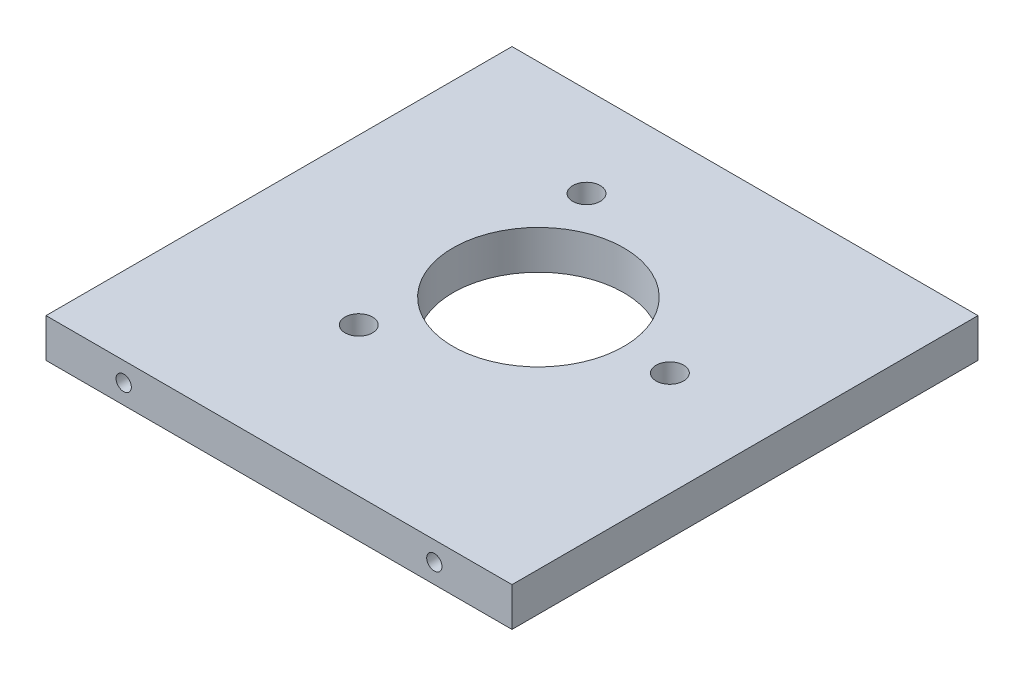
SolidWorks part; units mm, degrees
material "6061 Alloy"
ref_plane "Front Plane" through (0, 0, 0) normal (0, 0, 1) x (1, 0, 0)
ref_plane "Top Plane" through (0, 0, 0) normal (0, 1, 0) x (1, 0, 0)
ref_plane "Right Plane" through (0, 0, 0) normal (1, 0, 0) x (0, 0, -1)
sketch "Sketch1" plane through (0, 0, 0) normal (0, 0, 1) x (1, 0, 0)
  line L0 (0, 3.175) -> (0, -3.175)
  line L1 (-38.1, 0) -> (38.1, 0) construction
  point P6 (0, 0)
  dimension "Width" = 76.2
  dimension "Thk" = 6.35
sketch "Sketch2" plane through (0, 0, 0) normal (1, 0, 0) x (0, 0, -1)
  line L0 (76.2, 0) -> (-76.2, 0)
  point P4 (0, 0)
  dimension "Length" = 152.4
sketch "Sketch3" plane through (0, 0, 0) normal (0, 0, 1) x (1, 0, 0)
  line L1 (38.1, 3.175) -> (-38.1, 3.175)
  line L2 (38.1, 3.175) -> (38.1, -3.175)
  line L3 (38.1, -3.175) -> (-38.1, -3.175)
  line L4 (-38.1, 3.175) -> (-38.1, -3.175)
  line L5 (38.1, 3.175) -> (-38.1, -3.175) construction
  line L6 (38.1, -3.175) -> (-38.1, 3.175) construction
  point P0 (0, 0)
extrude "Boss-Extrude1" add sketch "Sketch3" along normal up to vertex (76.2 mm away) and the other way up to vertex (76.2 mm away) up to point (0, 0, 76.2) other way up to point (0, 0, -76.2)
sketch "Sketch4" plane through (0, 3.175, 0) normal (0, 1, 0) x (1, 0, 0)
  point P1 (0, -1.15)
hole_wizard "M8 Clearance Hole1" [suppressed] positions "Sketch5" profile "Sketch6" hole size "M8" standard "ANSI Metric"
sketch "Sketch5" plane through (0, 3.175, 0) normal (0, 1, 0) x (1, 0, 0)
  point P8 (0, -1.15)
sketch "Sketch6" plane through (0, 3.175, 1.15) normal (1, 0, 0) x (0, 0, 1)
  line L0 (0, 0) -> (0, 6.35)
  line L1 (0, 6.35) -> (4.5, 6.35)
  line L2 (4.5, 6.35) -> (4.5, 0)
  line L5 (4.5, 0) -> (0, 0)
  line L11 (0, -6.35) -> (0, 107.95) construction
  dimension "Thru Hole Dia." = 9
  dimension "Thru Hole Depth" = 6.35
sketch "Sketch7" plane through (0, 3.175, 0) normal (0, 1, 0) x (1, 0, 0)
  point P0 (-8.2489, -5.9125)
  point P1 (0, -10.675)
  point P3 (8.2489, -5.9125)
  point P5 (8.2489, 3.6125)
  point P7 (0, 8.375)
  point P9 (-8.2489, 3.6125)
hole_wizard "CSK for M3 Flat Head Machine Screw1" [suppressed] positions "Sketch8" profile "Sketch10" countersink size "M3" standard "ANSI Metric"
sketch "Sketch8" plane through (0, 3.175, 0) normal (0, 1, 0) x (1, 0, 0)
  point P0 (-8.2489, -5.9125)
  point P3 (0, -10.675)
  point P6 (8.2489, -5.9125)
  point P9 (8.2489, 3.6125)
  point P12 (0, 8.375)
  point P15 (-8.2489, 3.6125)
sketch "Sketch10" plane through (-8.2489, -3.175, 5.9125) normal (1, 0, 0) x (0, 0, -1)
  line L0 (0, 0) -> (0, 6.35)
  line L1 (0, 6.35) -> (1.7, 6.35)
  line L2 (1.7, 6.35) -> (1.7, 1.45)
  line L3 (1.7, 1.45) -> (3.15, 0)
  line L5 (3.15, 0) -> (0, 0)
  line L6 (-1.7, 1.45) -> (-3.15, 0) construction
  line L11 (0, -6.35) -> (0, 107.95) construction
  dimension "Thru Hole Dia." = 3.4
  dimension "Thru Hole Depth" = 6.35
  dimension "Near C'Sink Dia." = 6.3
  dimension "Near C'Sink Angle" = 90
sketch "Sketch11" plane through (0, -3.175, 0) normal (0, -1, 0) x (1, 0, 0)
  circle A0 centre (-0.451, 33.3341) radius 13.97
  point P0 (-0.451, 33.3341)
  dimension "D1" = 27.94
extrude "Cut-Extrude1" cut sketch "Sketch11" against normal through all
sketch "Sketch12" plane through (0, -3.175, 0) normal (0, -1, 0) x (1, 0, 0)
  point P0 (-11.201, 14.7145)
  point P1 (21.049, 33.3341)
  point P3 (-11.201, 51.9536)
hole_wizard "CSK for M4 Flat Head Machine Screw1" positions "Sketch13" profile "Sketch14" countersink size "M4" standard "ANSI Metric" end condition through all
sketch "Sketch13" plane through (0, -3.175, 0) normal (0, -1, 0) x (-1, 0, 0)
  point P0 (11.201, -14.7145)
  point P3 (-21.049, -33.3341)
  point P6 (11.201, -51.9536)
sketch "Sketch14" plane through (-11.201, -3.175, 14.7145) normal (1, 0, 0) x (0, 0, -1)
  line L0 (0, 0) -> (0, 6.35)
  line L1 (0, 6.35) -> (2.25, 6.35)
  line L2 (2.25, 6.35) -> (2.25, 2.45)
  line L3 (2.25, 2.45) -> (4.7, 0)
  line L5 (4.7, 0) -> (0, 0)
  line L6 (-2.25, 2.45) -> (-4.7, 0) construction
  line L11 (0, -6.35) -> (0, 107.95) construction
  dimension "Thru Hole Dia." = 4.5
  dimension "Thru Hole Depth" = 6.35
  dimension "Near C'Sink Dia." = 9.4
  dimension "Near C'Sink Angle" = 90
sketch "Sketch15" plane through (0, -3.175, 0) normal (0, -1, 0) x (1, 0, 0)
  point P0 (-0.451, 33.3341)
hole_wizard "Ø12.0mm Dowel Hole1" [suppressed] positions "Sketch18" profile "Sketch19" hole size "Ø12.0" standard "ANSI Metric"
sketch "Sketch18" plane through (0, -3.175, 0) normal (0, -1, 0) x (-1, 0, 0)
  point P0 (0.451, -31.8101)
sketch "Sketch19" plane through (-0.451, -3.175, 31.8101) normal (1, 0, 0) x (0, 0, -1)
  line L0 (0, 0) -> (0, 6.35)
  line L1 (0, 6.35) -> (6, 6.35)
  line L2 (6, 6.35) -> (6, 0)
  line L5 (6, 0) -> (0, 0)
  line L11 (0, -6.35) -> (0, 107.95) construction
  dimension "Thru Hole Dia." = 12
  dimension "Thru Hole Depth" = 6.35
sketch "Sketch20" plane through (0, -3.175, 0) normal (0, -1, 0) x (1, 0, 0)
  line L0 (-38.1, 76.2) -> (-38.1, -76.2) construction
  line L1 (38.1, -76.2) -> (-38.1, -76.2)
  line L2 (38.1, -76.2) -> (38.1, 0)
  line L3 (38.1, 0) -> (-38.1, 0)
  line L4 (-38.1, -76.2) -> (-38.1, 0)
  line L5 (-38.1, 76.2) -> (38.1, 76.2) construction
  dimension "D1" = 76.2
extrude "Cut-Extrude2" cut sketch "Sketch20" against normal through all
sketch "Sketch21" plane through (0, 3.175, 0) normal (0, 1, 0) x (1, 0, 0)
  circle A0 centre (0.6258, -38.1) radius 13.97
  point P0 (0.6258, -38.1)
  dimension "D1" = 27.94
extrude "Cut-Extrude3" [suppressed] cut sketch "Sketch21" against normal through all
sketch "Sketch22" plane through (0, 3.175, 0) normal (0, 1, 0) x (1, 0, 0)
  point P0 (0.6258, -59.6)
  point P1 (-17.9937, -27.35)
  point P3 (19.2454, -27.35)
hole_wizard "CSK for M4 Flat Head Machine Screw2" [suppressed] positions "Sketch23" profile "Sketch25" countersink size "M4" standard "ANSI Metric"
sketch "Sketch23" plane through (0, 3.175, 0) normal (0, 1, 0) x (1, 0, 0)
  point P0 (0.6258, -59.6)
  point P3 (19.2454, -27.35)
  point P6 (-17.9937, -27.35)
sketch "Sketch25" plane through (0.6258, 3.175, 59.6) normal (1, 0, 0) x (0, 0, 1)
  line L0 (0, 0) -> (0, 6.35)
  line L1 (0, 6.35) -> (2.25, 6.35)
  line L2 (2.25, 6.35) -> (2.25, 2.45)
  line L3 (2.25, 2.45) -> (4.7, 0)
  line L5 (4.7, 0) -> (0, 0)
  line L6 (-2.25, 2.45) -> (-4.7, 0) construction
  line L11 (0, -6.35) -> (0, 107.95) construction
  dimension "Thru Hole Dia." = 4.5
  dimension "Thru Hole Depth" = 6.35
  dimension "Near C'Sink Dia." = 9.4
  dimension "Near C'Sink Angle" = 90
sketch "Sketch26" [suppressed] plane through (0, 3.175, 0) normal (0, 1, 0) x (1, 0, 0)
  line L0 (38.1, -76.2) -> (38.1, 76.2) construction
  line L1 (-38.1, -76.2) -> (38.1, -76.2)
  line L2 (-38.1, -76.2) -> (-38.1, 25.4)
  line L3 (-38.1, 25.4) -> (38.1, 25.4)
  line L4 (38.1, -76.2) -> (38.1, 25.4)
  line L5 (38.1, 76.2) -> (-38.1, 76.2) construction
  dimension "D1" = 50.8
extrude "Cut-Extrude4" [suppressed] cut sketch "Sketch26" against normal through all contours L3 L4 L1 L2
sketch "Sketch27" [suppressed] plane through (-38.1, 0, 0) normal (-1, 0, 0) x (0, 0, 1)
  line L0 (-63.5, 0) -> (-38.1, 0) construction
  line L1 (-25.4, 3.175) -> (-76.2, 3.175) construction
  line L2 (-76.2, 3.175) -> (-76.2, -3.175) construction
  point P0 (-63.5, 0)
  point P1 (-38.1, 0)
  point P4 (-50.8, 0)
  point P7 (-50.8, 3.175)
  point P10 (-76.2, 0)
  dimension "D1" = 25.4
sketch "Sketch31" [suppressed] plane through (0, 3.175, 0) normal (0, 1, 0) x (1, 0, 0)
  line L0 (38.1, 76.2) -> (-38.1, 76.2) construction
  line L1 (38.1, 25.4) -> (5.08, 25.4)
  line L2 (38.1, 25.4) -> (38.1, 76.2)
  line L3 (38.1, 76.2) -> (5.08, 76.2)
  line L4 (5.08, 25.4) -> (5.08, 76.2)
  line L5 (-38.1, 25.4) -> (-38.1, 76.2) construction
  dimension "D1" = 43.18
extrude "Cut-Extrude5" [suppressed] cut sketch "Sketch31" against normal through all
hole_wizard "M3x0.5 Tapped Hole1" [suppressed] positions "Sketch28" profile "Sketch30" tap size "M3x0.5" standard "ANSI Metric"
sketch "Sketch28" [suppressed] plane through (-38.1, 0, 0) normal (-1, 0, 0) x (0, 0, 1)
  point P0 (-63.5, 0)
  point P3 (-38.1, 0)
cosmetic thread "Hole Thread1" [suppressed] parameters "D1"=4.0005, "D2"=3
cosmetic thread "Hole Thread2" [suppressed] parameters "D1"=4.0005, "D2"=3
sketch "Sketch30" plane through (-38.1, 0, -63.5) normal (0, 1, 0) x (0, 0, 1)
  line L0 (0, 0) -> (0, 6.35)
  line L1 (0, 6.35) -> (1.25, 5.5989)
  line L2 (1.25, 5.5989) -> (1.25, 0)
  line L5 (1.25, 0) -> (0, 0)
  line L10 (0, 6.35) -> (-1.25, 5.5989) construction
  line L11 (0, -6.35) -> (0, 107.95) construction
  dimension "Tap Drill Dia." = 2.5
  dimension "Tap Drill Depth" = 6.35
  dimension "Drill Angle" = 118
hole_wizard "M3x0.5 Tapped Hole2" [suppressed] positions "Sketch32" profile "Sketch33" tap size "M3x0.5" standard "ANSI Metric"
sketch "Sketch32" [suppressed] plane through (5.08, 0, 0) normal (1, 0, 0) x (0, 0, -1)
  point P0 (38.1, 0)
  point P3 (63.5, 0)
sketch "Sketch33" plane through (5.08, 0, -38.1) normal (0, 1, 0) x (0, 0, -1)
  line L0 (0, 0) -> (0, 12.7)
  line L1 (0, 12.7) -> (1.25, 11.9489)
  line L2 (1.25, 11.9489) -> (1.25, 0)
  line L5 (1.25, 0) -> (0, 0)
  line L10 (0, 12.7) -> (-1.25, 11.9489) construction
  line L11 (0, -6.35) -> (0, 107.95) construction
  dimension "Tap Drill Dia." = 2.5
  dimension "Tap Drill Depth" = 12.7
  dimension "Drill Angle" = 118
cosmetic thread "Hole Thread3" [suppressed] parameters "D1"=4.0005, "D2"=3
cosmetic thread "Hole Thread4" [suppressed] parameters "D1"=4.0005, "D2"=3
sketch "Sketch34" [suppressed] plane through (0, -3.175, 0) normal (0, -1, 0) x (1, 0, 0)
  point P0 (-12.7, 73.025)
  point P1 (12.7, 73.025)
  point P3 (-12.7, 3.175)
  point P5 (12.7, 3.175)
hole_wizard "CSK for M3 Flat Head Machine Screw3" [suppressed] positions "Sketch35" profile "Sketch36" countersink size "M3" standard "ANSI Metric"
sketch "Sketch35" [suppressed] plane through (0, -3.175, 0) normal (0, -1, 0) x (-1, 0, 0)
  point P0 (12.7, -73.025)
  point P3 (-12.7, -73.025)
  point P6 (12.7, -3.175)
  point P9 (-12.7, -3.175)
sketch "Sketch36" plane through (-12.7, -3.175, 73.025) normal (1, 0, 0) x (0, 0, -1)
  line L0 (0, 0) -> (0, 6.35)
  line L1 (0, 6.35) -> (1.7, 6.35)
  line L2 (1.7, 6.35) -> (1.7, 1.45)
  line L3 (1.7, 1.45) -> (3.15, 0)
  line L5 (3.15, 0) -> (0, 0)
  line L6 (-1.7, 1.45) -> (-3.15, 0) construction
  line L11 (0, -6.35) -> (0, 107.95) construction
  dimension "Thru Hole Dia." = 3.4
  dimension "Thru Hole Depth" = 6.35
  dimension "Near C'Sink Dia." = 6.3
  dimension "Near C'Sink Angle" = 90
sketch "Sketch37" plane through (0, 0, 76.2) normal (0, 0, 1) x (1, 0, 0)
  line L0 (25.4, 0) -> (-25.4, 0) construction
  line L1 (38.1, -3.175) -> (38.1, 3.175) construction
  line L2 (-38.1, -3.175) -> (38.1, -3.175) construction
  point P4 (38.1, 0)
  point P7 (0, -3.175)
  point P8 (0, 0)
  point P10 (25.4, 0)
  point P11 (-25.4, 0)
  dimension "D1" = 50.8
hole_wizard "M3x0.5 Tapped Hole3" positions "Sketch38" profile "Sketch40" tap size "M3x0.5" standard "ANSI Metric"
sketch "Sketch38" plane through (0, 0, 76.2) normal (0, 0, 1) x (1, 0, 0)
  point P0 (25.4, 0)
  point P3 (-25.4, 0)
sketch "Sketch40" plane through (25.4, 0, 76.2) normal (1, 0, 0) x (0, -1, 0)
  line L0 (0, 0) -> (0, 12.7)
  line L1 (0, 12.7) -> (1.25, 11.9489)
  line L2 (1.25, 11.9489) -> (1.25, 0)
  line L5 (1.25, 0) -> (0, 0)
  line L10 (0, 12.7) -> (-1.25, 11.9489) construction
  line L11 (0, -6.35) -> (0, 107.95) construction
  dimension "Tap Drill Dia." = 2.5
  dimension "Tap Drill Depth" = 12.7
  dimension "Drill Angle" = 118
cosmetic thread "Hole Thread5" parameters "D1"=5.9995, "D2"=3
cosmetic thread "Hole Thread6" parameters "D1"=5.9995, "D2"=3
sketch "Sketch41" [suppressed] plane through (0, -3.175, 0) normal (0, -1, 0) x (1, 0, 0)
  point P0 (25.4, -21.025)
  point P1 (25.4, -73.025)
  point P3 (-25.4, -73.025)
  point P5 (-25.4, -21.025)
hole_wizard "CSK for M3 Flat Head Machine Screw2" [suppressed] positions "Sketch42" profile "Sketch44" countersink size "M3" standard "ANSI Metric"
sketch "Sketch42" [suppressed] plane through (0, -3.175, 0) normal (0, -1, 0) x (-1, 0, 0)
  point P0 (-25.4, 21.025)
  point P3 (25.4, 21.025)
  point P6 (-25.4, 73.025)
  point P9 (25.4, 73.025)
sketch "Sketch44" plane through (25.4, -3.175, -21.025) normal (1, 0, 0) x (0, 0, -1)
  line L0 (0, 0) -> (0, 6.35)
  line L1 (0, 6.35) -> (1.7, 6.35)
  line L2 (1.7, 6.35) -> (1.7, 1.45)
  line L3 (1.7, 1.45) -> (3.15, 0)
  line L5 (3.15, 0) -> (0, 0)
  line L6 (-1.7, 1.45) -> (-3.15, 0) construction
  line L11 (0, -6.35) -> (0, 107.95) construction
  dimension "Thru Hole Dia." = 3.4
  dimension "Thru Hole Depth" = 6.35
  dimension "Near C'Sink Dia." = 6.3
  dimension "Near C'Sink Angle" = 90
sketch "Sketch45" [suppressed] plane through (0, -3.175, 0) normal (0, -1, 0) x (1, 0, 0)
  line L0 (25.4, 60.96) -> (-25.4, 60.96) construction
  line L1 (25.4, 58.46) -> (-25.4, 58.46)
  line L2 (25.4, 63.46) -> (-25.4, 63.46)
  line L3 (38.1, 76.2) -> (-38.1, 76.2) construction
  line L4 (0, -3.4925) -> (0, 3.4925) construction
  arc A0 (25.4, 58.46) -> (25.4, 63.46) centre (25.4, 60.96) ccw
  arc A1 (-25.4, 63.46) -> (-25.4, 58.46) centre (-25.4, 60.96) ccw
  point P2 (0, 60.96)
  dimension "D1" = 5
  dimension "D2" = 50.8
  dimension "D3" = 15.24
extrude "Cut-Extrude6" [suppressed] cut sketch "Sketch45" against normal through all
sketch "Sketch46" [suppressed] plane through (0, 3.175, 0) normal (0, 1, 0) x (1, 0, 0)
  line L0 (0, -69.85) -> (0, -31.75) construction
  line L1 (-1.5, -69.85) -> (-1.5, -31.75)
  line L2 (1.5, -69.85) -> (1.5, -31.75)
  line L3 (38.1, -76.2) -> (-38.1, -76.2) construction
  arc A0 (-1.5, -69.85) -> (1.5, -69.85) centre (0, -69.85) ccw
  arc A1 (1.5, -31.75) -> (-1.5, -31.75) centre (0, -31.75) ccw
  point P3 (0, -50.8)
  dimension "D1" = 3
  dimension "D2" = 38.1
  dimension "D3" = 6.35
extrude "Cut-Extrude7" [suppressed] cut sketch "Sketch46" against normal through all contours L2 A1 L1 A0
sketch "Sketch47" [suppressed] plane through (0, 3.175, 0) normal (0, 1, 0) x (1, 0, 0)
  line L0 (-19.05, -57.15) -> (-19.05, -25.4) construction
  line L1 (-28.575, -57.15) -> (-28.575, -25.4)
  line L2 (-9.525, -57.15) -> (-9.525, -25.4)
  line L3 (19.05, -57.15) -> (19.05, -25.4) construction
  line L4 (9.525, -57.15) -> (9.525, -25.4)
  line L5 (28.575, -57.15) -> (28.575, -25.4)
  line L6 (-19.05, -41.275) -> (19.05, -41.275) construction
  line L7 (0, -3.4925) -> (0, 3.4925) construction
  line L8 (38.1, -76.2) -> (-38.1, -76.2) construction
  line L9 (-19.05, 50.8) -> (19.05, 50.8) construction
  line L10 (-19.05, 63.5) -> (19.05, 63.5)
  line L11 (-19.05, 38.1) -> (19.05, 38.1)
  line L12 (38.1, 76.2) -> (-38.1, 76.2) construction
  line L13 (38.1, -76.2) -> (38.1, 76.2) construction
  arc A0 (-28.575, -57.15) -> (-9.525, -57.15) centre (-19.05, -57.15) ccw
  arc A1 (-9.525, -25.4) -> (-28.575, -25.4) centre (-19.05, -25.4) ccw
  arc A2 (9.525, -57.15) -> (28.575, -57.15) centre (19.05, -57.15) ccw
  arc A3 (28.575, -25.4) -> (9.525, -25.4) centre (19.05, -25.4) ccw
  arc A4 (-19.05, 63.5) -> (-19.05, 38.1) centre (-19.05, 50.8) ccw
  arc A5 (19.05, 38.1) -> (19.05, 63.5) centre (19.05, 50.8) ccw
  point P2 (-19.05, -41.275)
  point P7 (19.05, -41.275)
  point P16 (0, -41.275)
  point P23 (0, 50.8)
  dimension "D1" = 19.05
  dimension "D2" = 31.75
  dimension "D3" = 19.05
  dimension "D4" = 19.05
  dimension "D5" = 25.4
  dimension "D6" = 38.1
  dimension "D7" = 25.4
  dimension "D8" = 19.05
extrude "Cut-Extrude8" [suppressed] cut sketch "Sketch47" against normal through all
